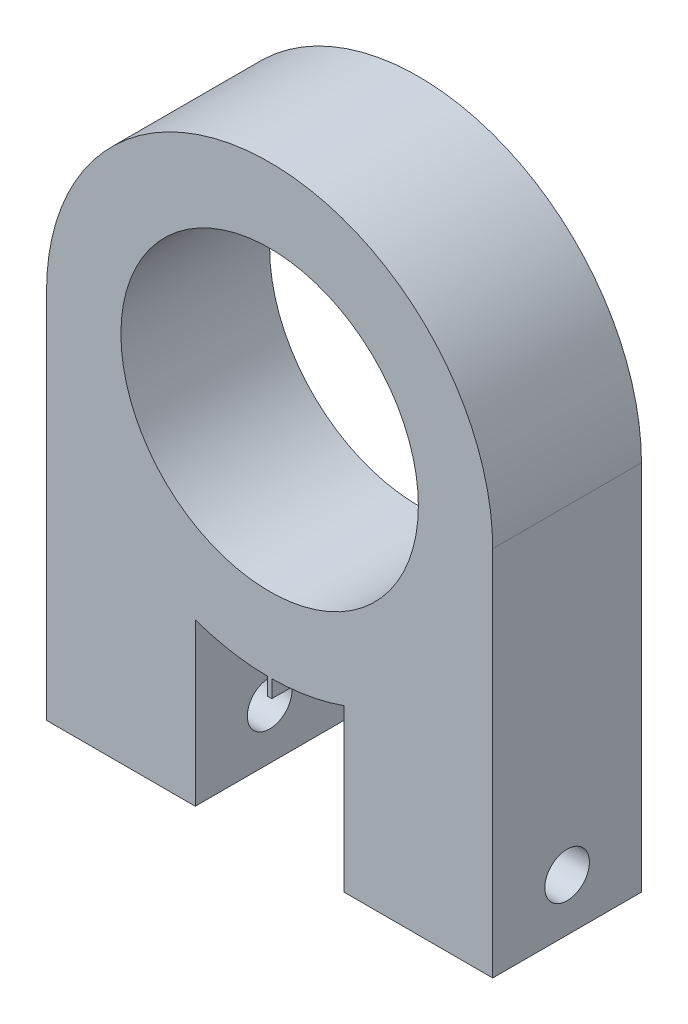
SolidWorks part; units mm, degrees
ref_plane "Plan de face" through (0, 0, 0) normal (0, 0, 1) x (1, 0, 0)
ref_plane "Plan de dessus" through (0, 0, 0) normal (0, 1, 0) x (1, 0, 0)
ref_plane "Plan de droite" through (0, 0, 0) normal (1, 0, 0) x (0, 0, -1)
sketch "Esquisse1" plane through (0, 0, 0) normal (0, 0, 1) x (1, 0, 0)
  circle A0 centre (0, 0) radius 10
  circle A1 centre (0, 0) radius 15
  dimension "D1" = 20
  dimension "D2" = 30
extrude "Boss.-Extru.1" add sketch "Esquisse1" along normal blind 10
sketch "Esquisse2" plane through (0, 0, 10) normal (0, 0, 1) x (1, 0, 0)
  line L12 (15, 0) -> (15, -25)
  line L26 (0, 20.4609) -> (0, -20.4609) construction
  line L63 (-0.1424, -14.6382) -> (-0.1424, -16.1644)
  line L64 (0.1424, -14.6382) -> (-0.1424, -14.6382)
  line L65 (0.1424, -14.6382) -> (0.1424, -16.1644)
  line L66 (0.1424, -16.1644) -> (-0.1424, -16.1644)
  line L67 (-10, 0) -> (-15, 0)
  line L68 (-5, -8.6603) -> (-5, -25)
  line L69 (-5, -25) -> (-15, -25)
  line L70 (-15, 0) -> (-15, -25)
  line L71 (5, -25) -> (15, -25)
  line L72 (5, -8.6603) -> (5, -25)
  line L73 (10, 0) -> (15, 0)
  circle A0 centre (0, 0) radius 15 construction
  arc A1 (-5, -8.6603) -> (-10, 0) centre (0, 0) cw
  circle A2 centre (0, 0) radius 10 construction
  arc A3 (5, -8.6603) -> (10, 0) centre (0, 0) ccw
  point P4 (0, 0)
  dimension "D1" = 10
  dimension "D2" = 25
extrude "Boss.-Extru.2" add sketch "Esquisse2" against normal blind 10
sketch "Esquisse3" plane through (-15, 0, 0) normal (-1, 0, 0) x (0, 0, 1)
  line L0 (0, -25) -> (10, -25) construction
  line L1 (0, -21.5) -> (10, -21.5) construction
  line L2 (0, 0) -> (0, -25) construction
  line L3 (10, 0) -> (10, -25) construction
  circle A0 centre (5, -21.5) radius 1.5
  dimension "D2" = 3
  dimension "D1" = 3.5
extrude "Enlèv. mat.-Extru.1" cut sketch "Esquisse3" against normal through all
